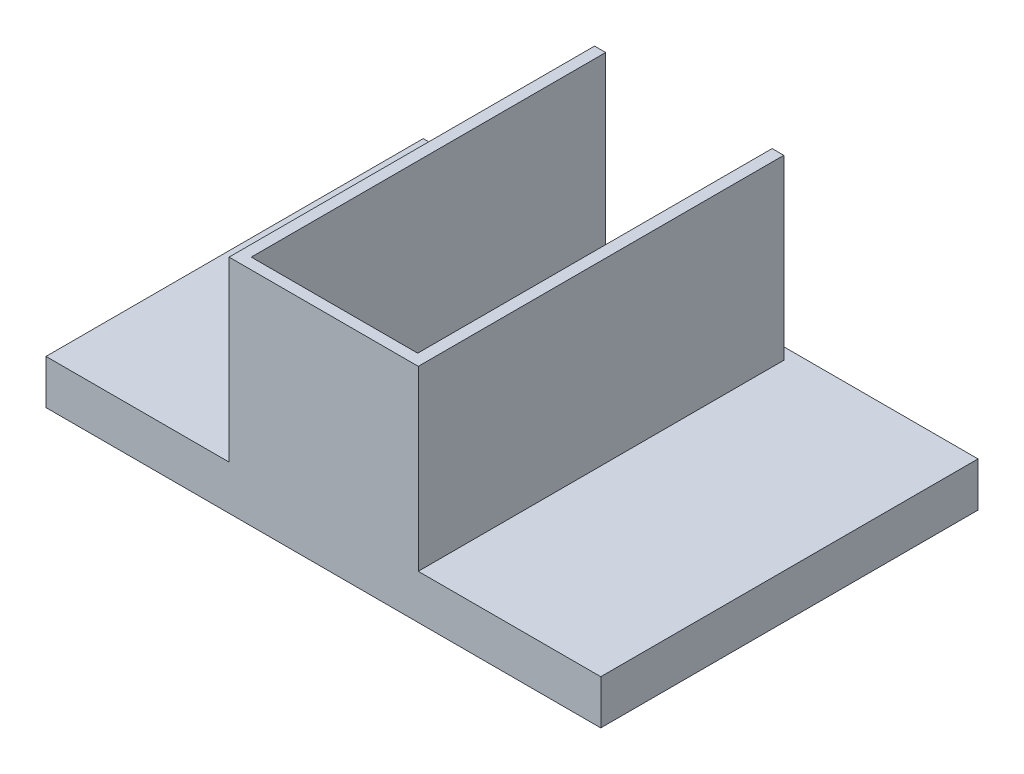
SolidWorks part; units mm, degrees
ref_plane "Front Plane" through (0, 0, 0) normal (0, 0, 1) x (1, 0, 0)
ref_plane "Top Plane" through (0, 0, 0) normal (0, 1, 0) x (1, 0, 0)
ref_plane "Right Plane" through (0, 0, 0) normal (1, 0, 0) x (0, 0, -1)
sketch "Sketch1" plane through (0, 0, 0) normal (0, 1, 0) x (1, 0, 0)
  line L0 (-60.7292, -26.4383) -> (2.7708, -26.4383)
  line L1 (-60.7292, -26.4383) -> (-60.7292, -4.8483)
  line L2 (2.7708, -26.4383) -> (2.7708, -4.8483)
  line L3 (-60.7292, -4.8483) -> (2.7708, -4.8483)
  dimension "D1" = 63.5
  dimension "D2" = 21.59
extrude "Boss-Extrude1" add sketch "Sketch1" along normal blind 5.08
sketch "Sketch2" plane through (0, 0, 26.4383) normal (0, 0, 1) x (1, 0, 0)
  line L0 (-38.5042, 5.08) -> (-19.4542, 5.08)
  line L1 (-38.5042, 5.08) -> (-38.5042, 25.4)
  line L2 (-19.4542, 5.08) -> (-19.4542, 25.4)
  line L3 (-38.5042, 25.4) -> (-19.4542, 25.4)
  line L4 (-60.7292, 5.08) -> (2.7708, 5.08) construction
  dimension "D1" = 19.05
  dimension "D2" = 22.225
  dimension "D3" = 20.32
extrude "Boss-Extrude2" add sketch "Sketch2" against normal blind 1.27
sketch "Sketch3" plane through (0, 5.08, 0) normal (0, 1, 0) x (1, 0, 0)
  line L0 (-38.5042, -26.4383) -> (-39.7742, -26.4383)
  line L1 (-38.5042, -26.4383) -> (-38.5042, -4.8483)
  line L2 (-39.7742, -26.4383) -> (-39.7742, -4.8483)
  line L3 (-38.5042, -4.8483) -> (-39.7742, -4.8483)
  line L4 (-60.7292, -26.4383) -> (-38.5042, -26.4383) construction
  dimension "D1" = 21.59
  dimension "D2" = 1.27
extrude "Boss-Extrude3" add sketch "Sketch3" along normal blind 20.32
mirror "Mirror2" about plane through (-60.7292, 5.08, 4.8483) normal (0, 0, 1) of "Boss-Extrude1", "Boss-Extrude2", "Boss-Extrude3"
sketch "Sketch4" plane through (0, 5.08, 0) normal (0, 1, 0) x (1, 0, 0)
  line L0 (-19.4542, -26.4383) -> (-18.1182, -26.4383)
  line L1 (-19.4542, -26.4383) -> (-19.4542, 16.6983)
  line L2 (-18.1182, -26.4383) -> (-18.1182, 16.6983)
  line L3 (-19.4542, 16.6983) -> (-18.1182, 16.6983)
  line L4 (-19.4542, -26.4383) -> (2.7708, -26.4383) construction
extrude "Boss-Extrude4" add sketch "Sketch4" along normal blind 20.32
sketch "Sketch5" plane through (0, 0, -16.7417) normal (0, 0, -1) x (-1, 0, 0)
  line L0 (24.5334, 5.1719) -> (34.6934, 5.1719)
  line L1 (24.5334, 5.1719) -> (24.5334, 25.3871)
  line L2 (34.6934, 5.1719) -> (34.6934, 25.3871)
  line L3 (24.5334, 25.3871) -> (34.6934, 25.3871)
  dimension "D1" = 10.16
  dimension "D2" = 5.08
extrude "Cut-Extrude2" cut sketch "Sketch5" against normal blind 1.27
sketch "Sketch6" plane through (0, 25.4, 0) normal (0, 1, 0) x (1, 0, 0)
  line L0 (-18.1182, -26.4383) -> (-18.1182, 16.6983) construction
  line L1 (-39.7742, 16.7417) -> (-18.1182, 16.7417)
  line L2 (-39.7742, 16.7417) -> (-39.7742, 15.3995)
  line L3 (-39.7742, 15.3995) -> (-18.1182, 15.3995)
  line L4 (-18.1182, 16.7417) -> (-18.1182, 15.3995)
extrude "Cut-Extrude3" cut sketch "Sketch6" against normal blind 20.32
